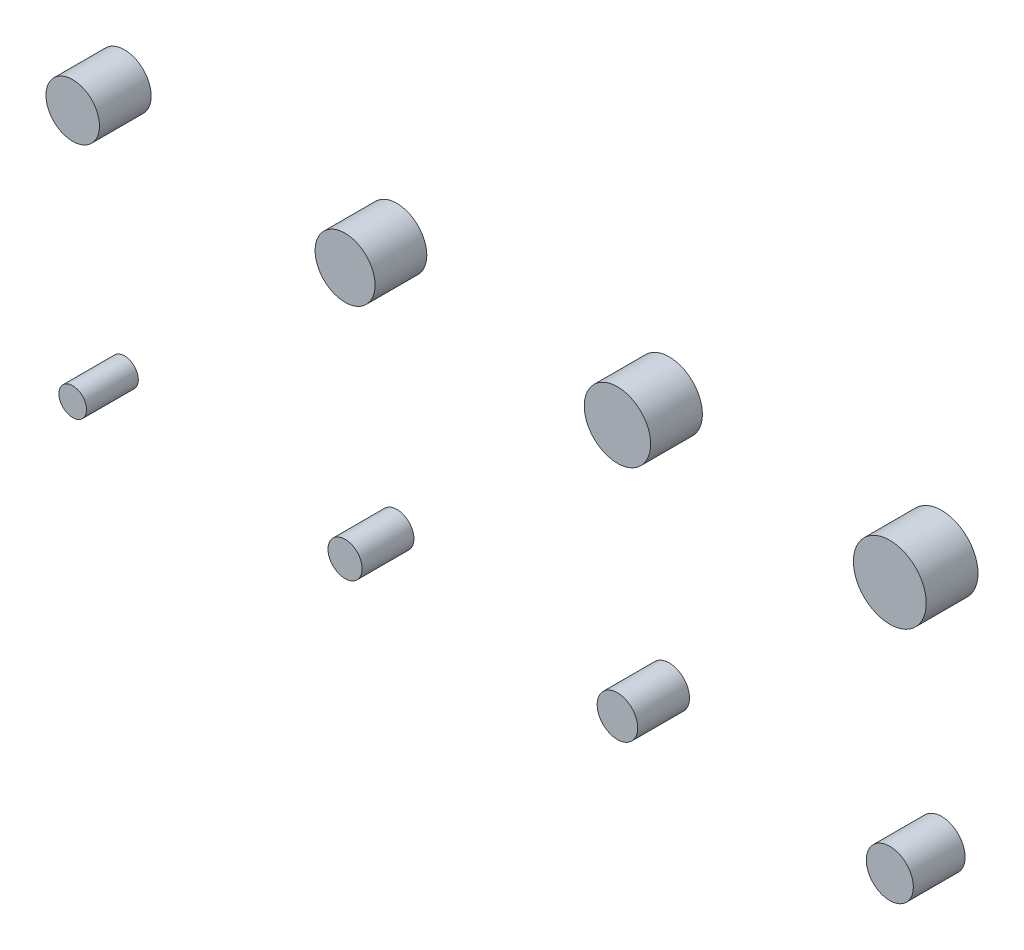
SolidWorks part; units mm, degrees
ref_plane "Front Plane" through (0, 0, 0) normal (0, 0, 1) x (1, 0, 0)
ref_plane "Top Plane" through (0, 0, 0) normal (0, 1, 0) x (1, 0, 0)
ref_plane "Right Plane" through (0, 0, 0) normal (1, 0, 0) x (0, 0, -1)
sketch "CurveSketch" plane through (0, 0, 0) normal (0, 0, 1) x (1, 0, 0)
  circle A0 centre (-87.193, -23.719) radius 3.137
  circle A1 centre (-25.474, -23.719) radius 3.868
  circle A2 centre (36.245, -23.719) radius 4.599
  circle A3 centre (97.964, -23.719) radius 5.33
  circle A4 centre (-87.193, 33.418) radius 6.061
  circle A5 centre (-25.474, 33.418) radius 6.792
  circle A6 centre (36.245, 33.418) radius 7.523
  circle A7 centre (97.964, 33.418) radius 8.254
  dimension "D1" = 3.137
  dimension "D2" = 3.868
  dimension "D3" = 4.599
  dimension "D4" = 5.33
  dimension "D5" = 6.061
  dimension "D6" = 6.792
  dimension "D7" = 7.523
  dimension "D8" = 8.254
extrude "CurveBoss" add sketch "CurveSketch" along normal blind 11.731
